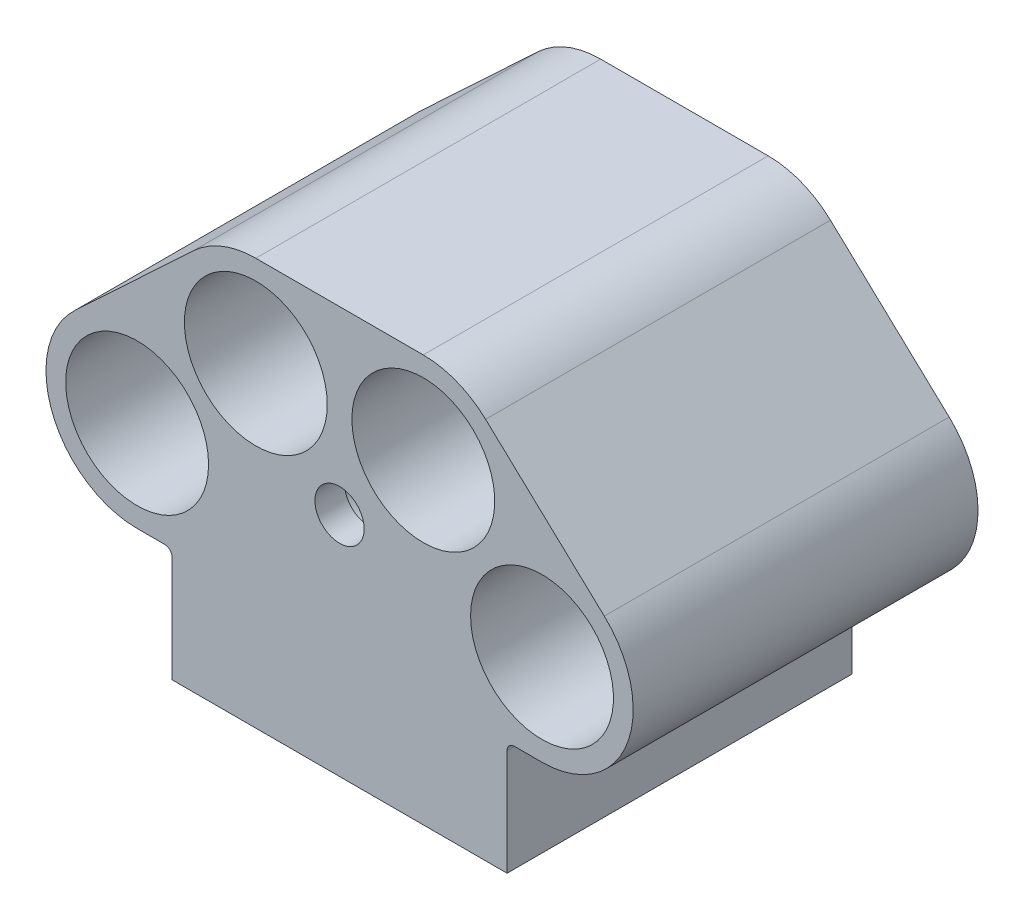
SolidWorks part; units mm, degrees
ref_plane "Front Plane" through (0, 0, 0) normal (0, 0, 1) x (1, 0, 0)
ref_plane "Top Plane" through (0, 0, 0) normal (0, 1, 0) x (1, 0, 0)
ref_plane "Right Plane" through (0, 0, 0) normal (1, 0, 0) x (0, 0, -1)
sketch "Sketch1" plane through (0, 0, 0) normal (0, 0, 1) x (1, 0, 0)
  line L0 (-11.9595, 12.7758) -> (-50.7466, -23.5332) construction
  line L1 (11.9595, 12.7758) -> (50.7466, -23.5332) construction
  line L2 (-11.9595, 12.7758) -> (11.9595, 12.7758) construction
  line L3 (-50.7466, -23.5332) -> (50.7466, -23.5332) construction
  line L4 (-17.5, -2) -> (17.5, -2) construction
  line L5 (0, 0) -> (0, -2) construction
  line L6 (-17.5, -2) -> (-17.5, 4) construction
  line L7 (-17.5, 4) -> (-20.5, 4) construction
  line L8 (-20.5, 4) -> (-20.5, -5) construction
  line L9 (-20.5, -5) -> (20.5, -5) construction
  line L10 (20.5, -5) -> (20.5, 4) construction
  line L11 (20.5, 4) -> (17.5, 4) construction
  line L12 (17.5, 4) -> (17.5, -2) construction
  line L13 (0, -2) -> (0, 40.1846) construction
  line L14 (-20.5457, 18.7784) -> (-8.5, 30.0545) construction
  line L15 (-26.8672, 25.5313) -> (-14.8215, 36.8074)
  line L16 (-20.5457, 9.5284) -> (-17.75, 9.5284)
  line L17 (-17, 8.7784) -> (-17, -2)
  line L18 (-17, -2) -> (0, -2)
  line L19 (-8.5, 39.3045) -> (0, 39.3045)
  line L20 (0, 39.3045) -> (0, -2)
  circle A0 centre (0, 0) radius 17.5 construction
  circle A1 centre (-20.5457, 18.7784) radius 7.25
  circle A2 centre (-8.5, 30.0545) radius 7.25
  circle A3 centre (-8.5, 30.0545) radius 9.25 construction
  circle A4 centre (-20.5457, 18.7784) radius 9.25 construction
  arc A5 (-17.75, 9.5284) -> (-17, 8.7784) centre (-17.75, 8.7784) cw
  arc A6 (-14.8215, 36.8074) -> (-8.5, 39.3045) centre (-8.5, 30.0545) cw
  arc A7 (-20.5457, 9.5284) -> (-26.8672, 25.5313) centre (-20.5457, 18.7784) cw
  dimension "D1" = 35
  dimension "D8" = 14.5
  dimension "D10" = 2
  dimension "D11" = 2
  dimension "D13" = 0.75
  dimension "D2" = 93.78
  dimension "D3" = 35
  dimension "2" = 2
  dimension "D4" = 6
  dimension "D5" = 3
  dimension "D6" = 3
  dimension "D7" = 3
  dimension "D9" = 17
  dimension "D12" = 0.5
extrude "Boss-Extrude1" add sketch "Sketch1" along normal mid plane 35 contours A7 L16 A5 L17 L18 L20 L19 A6 L15 A2 A1
mirror "Mirror1" about plane through (0, 0, 0) normal (1, 0, 0) of "Boss-Extrude1"
sketch "Sketch2" plane through (0, 0, -17.5) normal (0, 0, -1) x (-1, 0, 0)
  line L0 (0, -2) -> (0, 21) construction
  line L1 (17, -2) -> (-17, -2) construction
  circle A0 centre (0, 21) radius 2.5
  point P3 (0, 14.3571)
  dimension "D2" = 5
  dimension "D1" = 23
extrude "Cut-Extrude1" cut sketch "Sketch2" against normal through all
sketch "Sketch3" plane through (0, 0, -17.5) normal (0, 0, -1) x (-1, 0, 0)
  circle A0 centre (0, 21) radius 4
  dimension "D1" = 8
extrude "Cut-Extrude2" cut sketch "Sketch3" against normal offset from surface (29 mm away) 3 from offset 3
